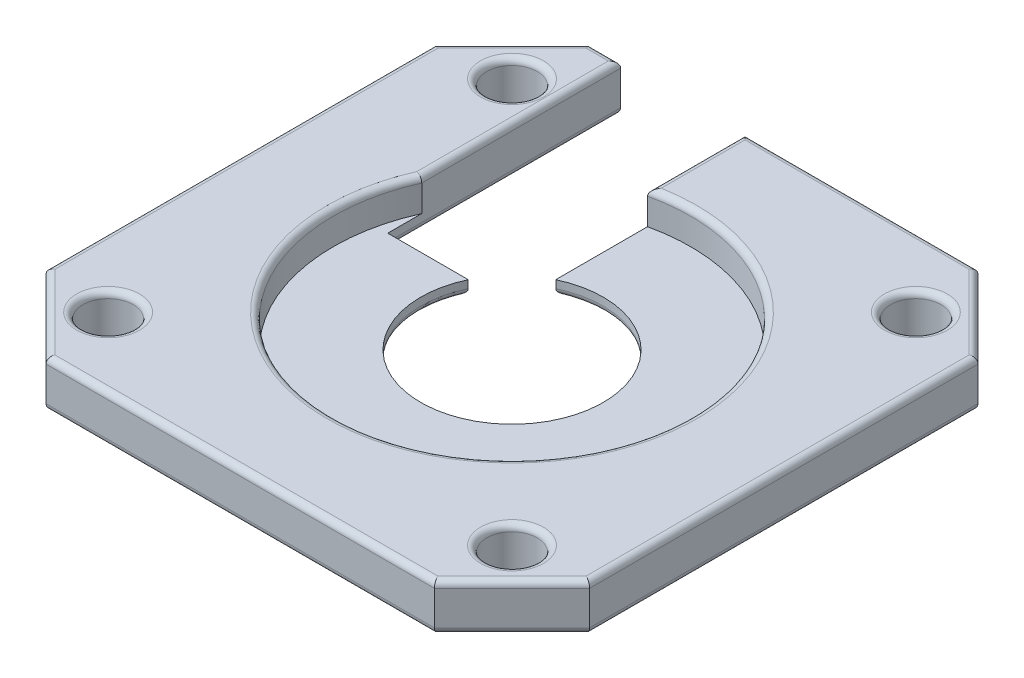
SolidWorks part; units mm, degrees
ref_plane "Front Plane" through (0, 0, 0) normal (0, 0, 1) x (1, 0, 0)
ref_plane "Top Plane" through (0, 0, 0) normal (0, 1, 0) x (1, 0, 0)
ref_plane "Right Plane" through (0, 0, 0) normal (1, 0, 0) x (0, 0, -1)
sketch "Sketch1" plane through (0, 0, 0) normal (0, 1, 0) x (1, 0, 0)
  line L0 (-30.5, 30.5) -> (-4.5, 30.5) construction
  line L1 (0, 0) -> (-35, 0)
  line L2 (0, 0) -> (0, 35)
  line L3 (0, 35) -> (-20, 35)
  line L4 (-35, 0) -> (-35, 35)
  line L5 (-4.5, 30.5) -> (-4.5, 4.5) construction
  line L6 (-4.5, 4.5) -> (-30.5, 4.5) construction
  line L7 (-30.5, 4.5) -> (-30.5, 30.5) construction
  line L8 (-30.5, 30.5) -> (-35, 30.5) construction
  line L9 (-30.5, 30.5) -> (-30.5, 35) construction
  line L10 (-4.5, 30.5) -> (0, 30.5) construction
  line L11 (-28, 35) -> (-28, 20)
  line L12 (-28, 20) -> (-20, 20)
  line L13 (-20, 20) -> (-20, 35)
  line L14 (-28, 35) -> (-35, 35)
  circle A0 centre (-30.5, 30.5) radius 1.625
  circle A1 centre (-4.5, 30.5) radius 1.625
  circle A2 centre (-4.5, 4.5) radius 1.625
  circle A3 centre (-30.5, 4.5) radius 1.625
  dimension "D2" = 3.25
  dimension "D1" = 35
  dimension "D3" = 26
  dimension "D4" = 7
  dimension "D5" = 8
  dimension "D6" = 15
extrude "Boss-Extrude1" add sketch "Sketch1" along normal blind 3
sketch "Sketch2" plane through (0, 3, 0) normal (0, 1, 0) x (1, 0, 0)
  line L4 (-35, 35) -> (0, 0) construction
  circle A0 centre (-17.5, 17.5) radius 11.5
  point P4 (-17.5, 17.5)
  point P5 (0, 0)
  point P6 (0, 0)
  point P7 (-35, 35)
  dimension "D1" = 23
extrude "Cut-Extrude1" cut sketch "Sketch2" against normal blind 2.1
sketch "Sketch3" plane through (0, 0, 0) normal (0, -1, 0) x (1, 0, 0)
  line L0 (-35, 0) -> (0, -35) construction
  circle A0 centre (-17.5, -17.5) radius 5.875
  dimension "D1" = 11.75
extrude "Cut-Extrude2" cut sketch "Sketch3" against normal through all
chamfer "Chamfer1" distance 5 angle 45 4 edges at (0, 1.5, 0) (-35, 1.5, 0) (0, 1.5, -35) (-35, 1.5, -35)
fillet "Fillet1" radius 0.4 33 edges at (-13.3457, 0, -13.3457) (-30.5, 3, -2.875) (-4.5, 3, -28.875) (-32.5, 3, -2.5) (-35, 3, -17.5) (-12.5, 3, -35) (-2.5, 3, -32.5) (0, 3, -17.5) (-2.5, 3, -2.5) (-17.5, 3, 0) (-30.5, 3, -28.875) (-4.5, 3, -2.875) (-10.225, 3, -8.5935) (-30.5, 0, -2.875) (-4.5, 0, -2.875) (-4.5, 0, -28.875) (-30.5, 0, -28.875) (-2.5, 0, -32.5) (-12.5, 0, -35) (-35, 0, -17.5) (-32.5, 0, -2.5) (-17.5, 0, 0) (-2.5, 0, -2.5) (0, 0, -17.5) (-20, 0, -28.9083) (-25.4083, 0, -20) (-28, 0, -27.5) (-29, 0, -35) (-29, 3, -35) (-28, 3, -28.5952) (-20, 3, -31.8625) (-32.5, 0, -32.5) (-32.5, 3, -32.5)
